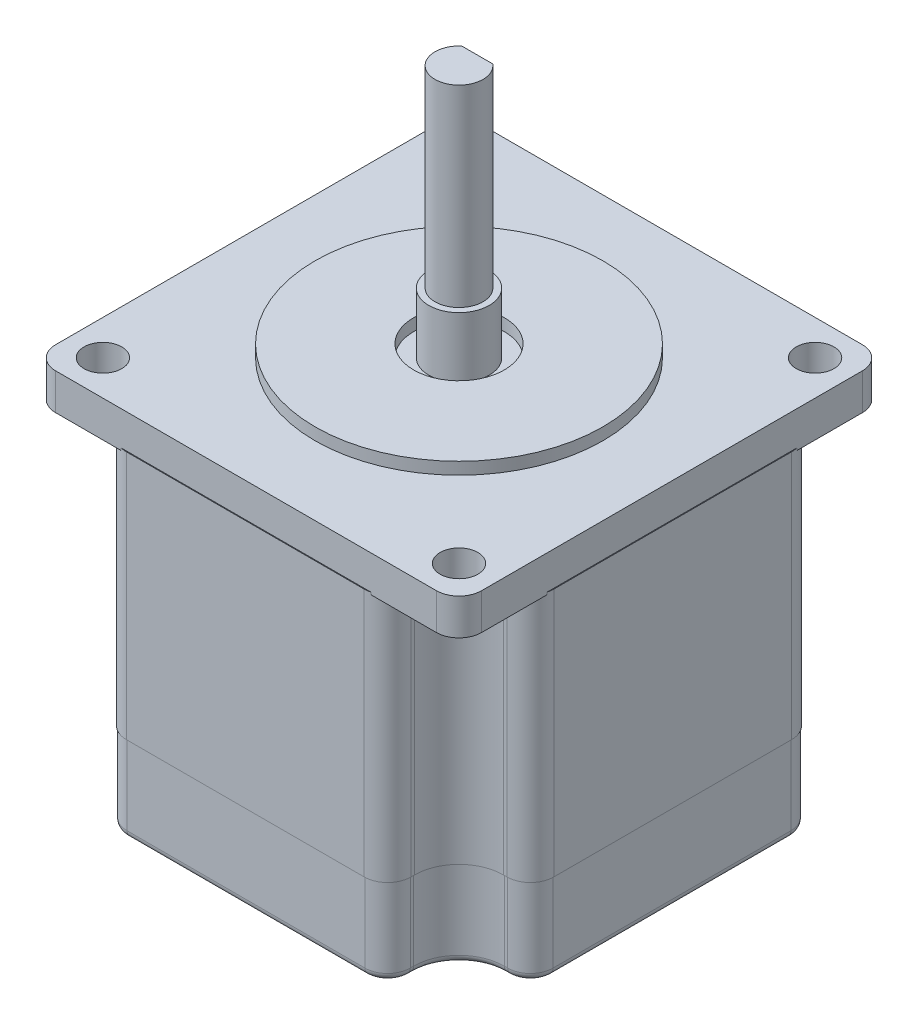
SolidWorks part; units mm, degrees
ref_plane "Front Plane" through (0, 0, 0) normal (0, 0, 1) x (1, 0, 0)
ref_plane "Top Plane" through (0, 0, 0) normal (0, 1, 0) x (1, 0, 0)
ref_plane "Right Plane" through (0, 0, 0) normal (1, 0, 0) x (0, 0, -1)
sketch "Sketch1" plane through (0, 0, 0) normal (0, 1, 0) x (1, 0, 0)
  line L5 (-28.2, 28.2) -> (28.2, 28.2)
  line L6 (-28.2, 28.2) -> (-28.2, -28.2)
  line L7 (-28.2, -28.2) -> (28.2, -28.2)
  line L8 (28.2, 28.2) -> (28.2, -28.2)
  line L9 (-28.2, 28.2) -> (28.2, -28.2) construction
  line L10 (-28.2, -28.2) -> (28.2, 28.2) construction
  point P0 (0, 0)
  dimension "D1" = 56.4
extrude "Boss-Extrude1" add sketch "Sketch1" along normal mid plane 49
sketch "Sketch2" plane through (0, 24.5, 0) normal (0, -1, 0) x (1, 0, 0)
  line L0 (-18.75, 28.2) -> (-18.75, 24.75)
  line L1 (-28.2, 28.2) -> (28.2, 28.2) construction
  line L2 (-24.75, 18.75) -> (-28.2, 18.75)
  line L3 (-28.2, -28.2) -> (-28.2, 28.2) construction
  line L4 (0, 0) -> (0, 28.2) construction
  line L5 (-18.75, 28.2) -> (-28.2, 28.2)
  line L6 (-28.2, 28.2) -> (-28.2, 18.75)
  line L7 (28.2, 28.2) -> (28.2, 18.75)
  line L8 (18.75, 28.2) -> (28.2, 28.2)
  line L9 (24.75, 18.75) -> (28.2, 18.75)
  line L10 (18.75, 28.2) -> (18.75, 24.75)
  line L11 (0, 0) -> (28.2, 0) construction
  line L12 (28.2, 28.2) -> (28.2, -28.2) construction
  line L13 (18.75, -28.2) -> (18.75, -24.75)
  line L14 (24.75, -18.75) -> (28.2, -18.75)
  line L15 (18.75, -28.2) -> (28.2, -28.2)
  line L16 (28.2, -28.2) -> (28.2, -18.75)
  line L17 (-28.2, -28.2) -> (-28.2, -18.75)
  line L18 (-18.75, -28.2) -> (-28.2, -28.2)
  line L19 (-24.75, -18.75) -> (-28.2, -18.75)
  line L20 (-18.75, -28.2) -> (-18.75, -24.75)
  arc A0 (-18.75, 24.75) -> (-24.75, 18.75) centre (-24.75, 24.75) cw
  arc A1 (18.75, 24.75) -> (24.75, 18.75) centre (24.75, 24.75) ccw
  arc A2 (18.75, -24.75) -> (24.75, -18.75) centre (24.75, -24.75) cw
  arc A3 (-18.75, -24.75) -> (-24.75, -18.75) centre (-24.75, -24.75) ccw
  dimension "D1" = 37.5
  dimension "D3" = 6
  dimension "D2" = 18.75
extrude "Cut-Extrude1" cut sketch "Sketch2" along normal through all from offset 4.8
fillet "Fillet1" radius 3 12 edges at (-28.2, -2.4, -18.75) (-28.2, -2.4, 18.75) (18.75, -2.4, 28.2) (28.2, -2.4, 18.75) (28.2, -2.4, -18.75) (18.75, -2.4, -28.2) (-18.75, -2.4, -28.2) (-18.75, -2.4, 28.2) (28.2, 22.1, 28.2) (-28.2, 22.1, -28.2) (28.2, 22.1, -28.2) (-28.2, 22.1, 28.2)
fillet "Fillet2" radius 1 24 edges at (-17.8713, -24.5, 27.3213) (-18.75, -24.5, 24.975) (-20.5074, -24.5, 20.5074) (-24.975, -24.5, 18.75) (-27.3213, -24.5, 17.8713) (-28.2, -24.5, 0) (-27.3213, -24.5, -17.8713) (-24.975, -24.5, -18.75) (-20.5074, -24.5, -20.5074) (-18.75, -24.5, -24.975) (-17.8713, -24.5, -27.3213) (0, -24.5, -28.2) (17.8713, -24.5, -27.3213) (18.75, -24.5, -24.975) (20.5074, -24.5, -20.5074) (24.975, -24.5, -18.75) (27.3213, -24.5, -17.8713) (28.2, -24.5, 0) (27.3213, -24.5, 17.8713) (24.975, -24.5, 18.75) (20.5074, -24.5, 20.5074) (18.75, -24.5, 24.975) (17.8713, -24.5, 27.3213) (0, -24.5, 28.2)
sketch "Sketch3" plane through (0, 24.5, 0) normal (0, 1, 0) x (1, 0, 0)
  line L0 (0, 0) -> (0, 23.57) construction
  line L1 (-23.57, 23.57) -> (23.57, 23.57) construction
  line L2 (-23.57, 23.57) -> (-23.57, -23.57) construction
  line L3 (-23.57, -23.57) -> (23.57, -23.57) construction
  line L4 (23.57, 23.57) -> (23.57, -23.57) construction
  line L5 (-23.57, 23.57) -> (23.57, -23.57) construction
  line L6 (-23.57, -23.57) -> (23.57, 23.57) construction
  line L7 (0, 0) -> (23.57, 0) construction
  circle A0 centre (23.57, 23.57) radius 2.5
  circle A1 centre (-23.57, 23.57) radius 2.5
  circle A2 centre (23.57, -23.57) radius 2.5
  circle A3 centre (-23.57, -23.57) radius 2.5
  point P0 (0, 0)
  dimension "D2" = 5
  dimension "D1" = 47.14
extrude "Cut-Extrude2" cut sketch "Sketch3" against normal blind 55.8
sketch "Sketch4" plane through (0, 24.5, 0) normal (0, 1, 0) x (1, 0, 0)
  circle A0 centre (0, 0) radius 19.05
  dimension "D1" = 38.1
extrude "Boss-Extrude2" add sketch "Sketch4" along normal blind 1.6
sketch "Sketch5" plane through (0, 24.5, 0) normal (0, 1, 0) x (1, 0, 0)
  circle A0 centre (0, 0) radius 3.175
  dimension "D1" = 6.35
extrude "Boss-Extrude3" add sketch "Sketch5" along normal blind 33.5
sketch "Sketch6" plane through (0, 58, 0) normal (0, 1, 0) x (1, 0, 0)
  line L0 (-2.0494, 2.425) -> (2.0494, 2.425)
  circle A0 centre (0, 0) radius 3.175 construction
  circle A1 centre (0, 0) radius 3.175 construction
  arc A2 (2.0494, 2.425) -> (-2.0494, 2.425) centre (0, 0) ccw
  dimension "D1" = 5.6
extrude "Cut-Extrude3" cut sketch "Sketch6" against normal blind 15
sketch "Sketch7" plane through (0, 0, 0) normal (1, 0, 0) x (0, 0, -1)
  line L0 (2.425, 43) -> (3.175, 41)
  line L1 (3.175, 26.1) -> (3.175, 43) construction
  line L2 (3.175, 41) -> (3.175, 43)
  line L3 (3.175, 43) -> (2.425, 43)
  dimension "D1" = 2
extrude "Cut-Extrude4" cut sketch "Sketch7" against normal through all both and the other way through all
fillet "Fillet3" radius 5 1 edges at (0, 43, -2.425)
sketch "Sketch8" plane through (0, 26.1, 0) normal (0, 1, 0) x (1, 0, 0)
  circle A0 centre (0, 0) radius 3.175 construction
  circle A1 centre (0, 0) radius 3.175
  circle A2 centre (0, 0) radius 6
  dimension "D1" = 12
extrude "Cut-Extrude5" cut sketch "Sketch8" against normal up to surface (1.6 mm away) up to face at (0, 24.5, 19.05)
sketch "Sketch9" plane through (0, 24.5, 0) normal (0, 1, 0) x (1, 0, 0)
  line L0 (25.2, 28.2) -> (-25.2, 28.2) construction
  line L2 (-19.5, 28.2) -> (-12.5, 28.2)
  line L3 (-19.5, 28.2) -> (-19.5, 25.7)
  line L5 (-12.5, 28.2) -> (-12.5, 25.7)
  line L6 (0, 0) -> (0, 28.2) construction
  line L7 (12.5, 28.2) -> (12.5, 25.7)
  line L8 (19.5, 28.2) -> (19.5, 25.7)
  line L9 (19.5, 28.2) -> (12.5, 28.2)
  line L10 (0, 0) -> (28.2, 0) construction
  line L11 (28.2, -25.2) -> (28.2, 25.2) construction
  line L12 (19.5, -28.2) -> (12.5, -28.2)
  line L13 (19.5, -28.2) -> (19.5, -25.7)
  line L14 (12.5, -28.2) -> (12.5, -25.7)
  line L15 (-12.5, -28.2) -> (-12.5, -25.7)
  line L16 (-19.5, -28.2) -> (-19.5, -25.7)
  line L17 (-19.5, -28.2) -> (-12.5, -28.2)
  arc A0 (-19.5, 25.7) -> (-12.5, 25.7) centre (-16, 25.7) ccw
  arc A1 (19.5, 25.7) -> (12.5, 25.7) centre (16, 25.7) cw
  arc A2 (19.5, -25.7) -> (12.5, -25.7) centre (16, -25.7) ccw
  arc A3 (-19.5, -25.7) -> (-12.5, -25.7) centre (-16, -25.7) cw
  dimension "D3" = 25
  dimension "D1" = 6
  dimension "D2" = 7
extrude "Cut-Extrude6" [suppressed] cut sketch "Sketch9" against normal blind 2.5
sketch "Sketch10" plane through (0, -24.5, 0) normal (0, -1, 0) x (1, 0, 0)
  line L1 (28.2, -15.75) -> (28.2, 15.75) construction
  line L3 (25.2, 18.75) -> (24.75, 18.75) construction
  line L5 (18.75, 24.75) -> (18.75, 25.2) construction
  line L9 (-28.2, 15.75) -> (-28.2, -15.75) construction
  line L11 (-24.75, 18.75) -> (-25.2, 18.75) construction
  line L13 (-18.75, 25.2) -> (-18.75, 24.75) construction
  line L14 (15.75, 28.2) -> (-15.75, 28.2) construction
  line L17 (28.2, -15.75) -> (28.2, 15.75)
  line L19 (25.2, 18.75) -> (24.75, 18.75)
  line L21 (18.75, 24.75) -> (18.75, 25.2)
  line L25 (-28.2, 15.75) -> (-28.2, -15.75)
  line L27 (-24.75, 18.75) -> (-25.2, 18.75)
  line L29 (-18.75, 25.2) -> (-18.75, 24.75)
  line L30 (15.75, 28.2) -> (-15.75, 28.2)
  line L32 (0, 0) -> (28.2, 0) construction
  line L33 (15.75, -28.2) -> (-15.75, -28.2)
  line L34 (-18.75, -25.2) -> (-18.75, -24.75)
  line L35 (-24.75, -18.75) -> (-25.2, -18.75)
  line L36 (18.75, -24.75) -> (18.75, -25.2)
  line L37 (25.2, -18.75) -> (24.75, -18.75)
  line L38 (25.2, 18.85) -> (24.75, 18.85)
  line L39 (18.85, 24.75) -> (18.85, 25.2)
  line L40 (15.75, 28.3) -> (-15.75, 28.3)
  line L41 (-18.85, 25.2) -> (-18.85, 24.75)
  line L42 (-24.75, 18.85) -> (-25.2, 18.85)
  line L43 (-28.3, 15.75) -> (-28.3, -15.75)
  line L44 (-24.75, -18.85) -> (-25.2, -18.85)
  line L45 (-18.85, -25.2) -> (-18.85, -24.75)
  line L46 (15.75, -28.3) -> (-15.75, -28.3)
  line L47 (18.85, -24.75) -> (18.85, -25.2)
  line L48 (25.2, -18.85) -> (24.75, -18.85)
  line L49 (28.3, -15.75) -> (28.3, 15.75)
  arc A0 (28.2, 15.75) -> (25.2, 18.75) centre (25.2, 15.75) ccw construction
  arc A2 (18.75, 24.75) -> (24.75, 18.75) centre (24.75, 24.75) ccw construction
  arc A4 (18.75, 25.2) -> (15.75, 28.2) centre (15.75, 25.2) ccw construction
  arc A7 (-25.2, 18.75) -> (-28.2, 15.75) centre (-25.2, 15.75) ccw construction
  arc A9 (-24.75, 18.75) -> (-18.75, 24.75) centre (-24.75, 24.75) ccw construction
  arc A10 (-15.75, 28.2) -> (-18.75, 25.2) centre (-15.75, 25.2) ccw construction
  arc A12 (28.2, 15.75) -> (25.2, 18.75) centre (25.2, 15.75) ccw
  arc A14 (18.75, 24.75) -> (24.75, 18.75) centre (24.75, 24.75) ccw
  arc A16 (18.75, 25.2) -> (15.75, 28.2) centre (15.75, 25.2) ccw
  arc A19 (-25.2, 18.75) -> (-28.2, 15.75) centre (-25.2, 15.75) ccw
  arc A21 (-24.75, 18.75) -> (-18.75, 24.75) centre (-24.75, 24.75) ccw
  arc A22 (-15.75, 28.2) -> (-18.75, 25.2) centre (-15.75, 25.2) ccw
  arc A24 (-15.75, -28.2) -> (-18.75, -25.2) centre (-15.75, -25.2) cw
  arc A25 (-24.75, -18.75) -> (-18.75, -24.75) centre (-24.75, -24.75) cw
  arc A26 (-25.2, -18.75) -> (-28.2, -15.75) centre (-25.2, -15.75) cw
  arc A27 (18.75, -25.2) -> (15.75, -28.2) centre (15.75, -25.2) cw
  arc A28 (18.75, -24.75) -> (24.75, -18.75) centre (24.75, -24.75) cw
  arc A29 (28.2, -15.75) -> (25.2, -18.75) centre (25.2, -15.75) cw
  arc A30 (28.3, 15.75) -> (25.2, 18.85) centre (25.2, 15.75) ccw
  arc A31 (18.85, 24.75) -> (24.75, 18.85) centre (24.75, 24.75) ccw
  arc A32 (18.85, 25.2) -> (15.75, 28.3) centre (15.75, 25.2) ccw
  arc A33 (-15.75, 28.3) -> (-18.85, 25.2) centre (-15.75, 25.2) ccw
  arc A34 (-24.75, 18.85) -> (-18.85, 24.75) centre (-24.75, 24.75) ccw
  arc A35 (-25.2, 18.85) -> (-28.3, 15.75) centre (-25.2, 15.75) ccw
  arc A36 (-25.2, -18.85) -> (-28.3, -15.75) centre (-25.2, -15.75) cw
  arc A37 (-24.75, -18.85) -> (-18.85, -24.75) centre (-24.75, -24.75) cw
  arc A38 (-15.75, -28.3) -> (-18.85, -25.2) centre (-15.75, -25.2) cw
  arc A39 (18.85, -25.2) -> (15.75, -28.3) centre (15.75, -25.2) cw
  arc A40 (18.85, -24.75) -> (24.75, -18.85) centre (24.75, -24.75) cw
  arc A41 (28.3, -15.75) -> (25.2, -18.85) centre (25.2, -15.75) cw
  dimension "D1" = 0.1
extrude "Boss-Extrude4" add sketch "Sketch10" against normal blind 33 from offset 11.5 separate body offset against normal yes
sketch "Sketch11" plane through (0, 26.1, 0) normal (0, 1, 0) x (1, 0, 0)
  circle A0 centre (0, 0) radius 4
  dimension "D1" = 8
extrude "Boss-Extrude5" add sketch "Sketch11" along normal blind 6.4 and the other way up to surface (50.6 mm away)
sketch "Sketch12" plane through (0, 0, -28.2) normal (0, 0, -1) x (-1, 0, 0)
  line L0 (15.75, -24.5) -> (-15.75, -24.5) construction
  line L1 (-10.3, -24.5) -> (10.3, -24.5)
  line L2 (-10.3, -24.5) -> (-10.3, -13)
  line L3 (-10.3, -13) -> (10.3, -13)
  line L4 (10.3, -24.5) -> (10.3, -13)
  line L5 (-10.3, -24.5) -> (10.3, -13) construction
  line L6 (-10.3, -13) -> (10.3, -24.5) construction
  line L7 (15.75, -13) -> (-15.75, -13) construction
  point P0 (0, -18.75)
  dimension "D1" = 20.6
extrude "Boss-Extrude6" add sketch "Sketch12" along normal blind 5.4 and the other way up to vertex
